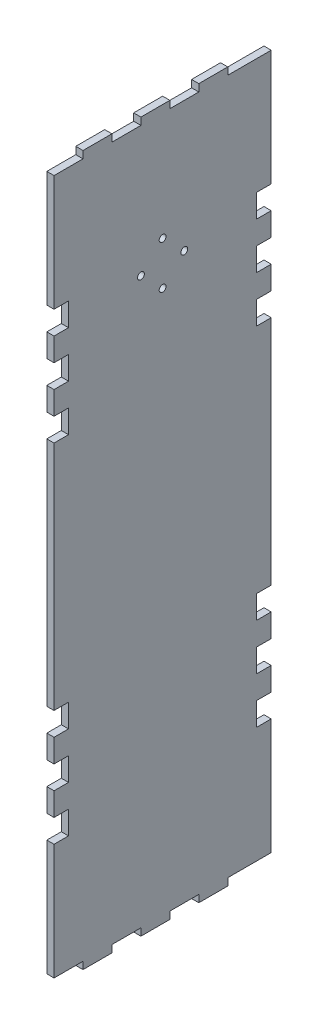
SolidWorks part; units mm, degrees
ref_plane "Front Plane" through (0, 0, 0) normal (0, 0, 1) x (1, 0, 0)
ref_plane "Top Plane" through (0, 0, 0) normal (0, 1, 0) x (1, 0, 0)
ref_plane "Right Plane" through (0, 0, 0) normal (1, 0, 0) x (0, 0, -1)
sketch "Sketch1" plane through (0, 0, 0) normal (1, 0, 0) x (0, 0, -1)
  line L1 (-47.625, -155.575) -> (47.625, -155.575)
  line L2 (-47.625, -155.575) -> (-47.625, 155.575)
  line L3 (-47.625, 155.575) -> (47.625, 155.575)
  line L4 (47.625, -155.575) -> (47.625, 155.575)
  line L5 (-47.625, -155.575) -> (47.625, 155.575) construction
  line L6 (-47.625, 155.575) -> (47.625, -155.575) construction
  point P0 (0, 0)
  dimension "D1" = 311.15
  dimension "D2" = 95.25
extrude "Boss-Extrude1" add sketch "Sketch1" along normal blind 3.175
sketch "Sketch2" plane through (3.175, 0, 0) normal (1, 0, 0) x (0, 0, -1)
  line L0 (-47.625, -155.575) -> (47.625, -155.575) construction
  line L1 (3.175, -155.575) -> (15.875, -155.575)
  line L2 (3.175, -155.575) -> (3.175, -152.4)
  line L3 (3.175, -152.4) -> (15.875, -152.4)
  line L4 (15.875, -155.575) -> (15.875, -152.4)
  line L6 (-9.525, -155.575) -> (-22.225, -155.575)
  line L7 (-9.525, -155.575) -> (-9.525, -152.4)
  line L8 (-9.525, -152.4) -> (-22.225, -152.4)
  line L9 (-22.225, -155.575) -> (-22.225, -152.4)
  line L10 (-47.625, -155.575) -> (-34.925, -155.575)
  line L11 (-47.625, -155.575) -> (-47.625, -152.4)
  line L12 (-47.625, -152.4) -> (-34.925, -152.4)
  line L13 (-34.925, -155.575) -> (-34.925, -152.4)
  line L14 (47.625, -155.575) -> (28.575, -155.575)
  line L15 (47.625, -155.575) -> (47.625, -152.4)
  line L16 (47.625, -152.4) -> (28.575, -152.4)
  line L17 (28.575, -155.575) -> (28.575, -152.4)
  point P10 (3.175, -153.9875)
  dimension "D1" = 3.175
  dimension "D2" = 12.7
  dimension "D3" = 12.7
  dimension "D4" = 12.7
  dimension "D5" = 12.7
  dimension "D6" = 12.7
extrude "Cut-Extrude1" cut sketch "Sketch2" against normal blind 3.175
mirror "Mirror1" about plane through (0, 0, 0) normal (0, 1, 0) of "Cut-Extrude1"
sketch "Sketch3" plane through (3.175, 0, 0) normal (1, 0, 0) x (0, 0, -1)
  line L0 (47.625, -152.4) -> (47.625, 152.4) construction
  line L1 (47.625, 101.6) -> (41.275, 101.6)
  line L2 (47.625, 101.6) -> (47.625, 91.44)
  line L3 (47.625, 91.44) -> (41.275, 91.44)
  line L4 (41.275, 101.6) -> (41.275, 91.44)
  line L6 (28.575, 155.575) -> (15.875, 155.575) construction
  line L7 (47.625, 81.28) -> (41.275, 81.28)
  line L8 (47.625, 81.28) -> (47.625, 71.12)
  line L9 (47.625, 71.12) -> (41.275, 71.12)
  line L10 (41.275, 81.28) -> (41.275, 71.12)
  line L15 (47.625, 60.96) -> (41.275, 60.96)
  line L16 (47.625, 60.96) -> (47.625, 50.8)
  line L17 (47.625, 50.8) -> (41.275, 50.8)
  line L18 (41.275, 60.96) -> (41.275, 50.8)
  dimension "D1" = 53.975
  dimension "D2" = 6.35
  dimension "D3" = 10.16
  dimension "D4" = 10.16
  dimension "D5" = 10.16
extrude "Cut-Extrude2" cut sketch "Sketch3" against normal blind 3.175
mirror "Mirror2" about plane through (0, 0, 0) normal (0, 0, 1) of "Cut-Extrude2"
mirror "Mirror3" about plane through (0, 0, 0) normal (0, 1, 0) of "Mirror2", "Cut-Extrude2"
sketch "Sketch5" plane through (3.175, 0, 0) normal (1, 0, 0) x (0, 0, -1)
  line L0 (0, 104.75) -> (-9.5, 95.25)
  line L1 (-9.5, 95.25) -> (0, 85.75)
  line L2 (0, 85.75) -> (9.5, 95.25)
  line L3 (9.5, 95.25) -> (0, 104.75)
  line L5 (47.625, 152.4) -> (28.575, 152.4) construction
  circle A0 centre (0, 104.75) radius 1.5
  circle A1 centre (9.5, 95.25) radius 1.5
  circle A2 centre (0, 85.75) radius 1.5
  circle A3 centre (-9.5, 95.25) radius 1.5
  point P8 (0, 0)
  point P10 (0, 0)
  dimension "D2" = 3
  dimension "D1" = 19
  dimension "D3" = 57.15
extrude "Cut-Extrude3" cut sketch "Sketch5" against normal blind 3.175 contours L3 A0 L0 | L0 A0 L3 | L2 A1 L3 | L3 A1 L2 | L0 A3 L1 | L1 A3 L0 | L1 A2 L2 | L2 A2 L1
